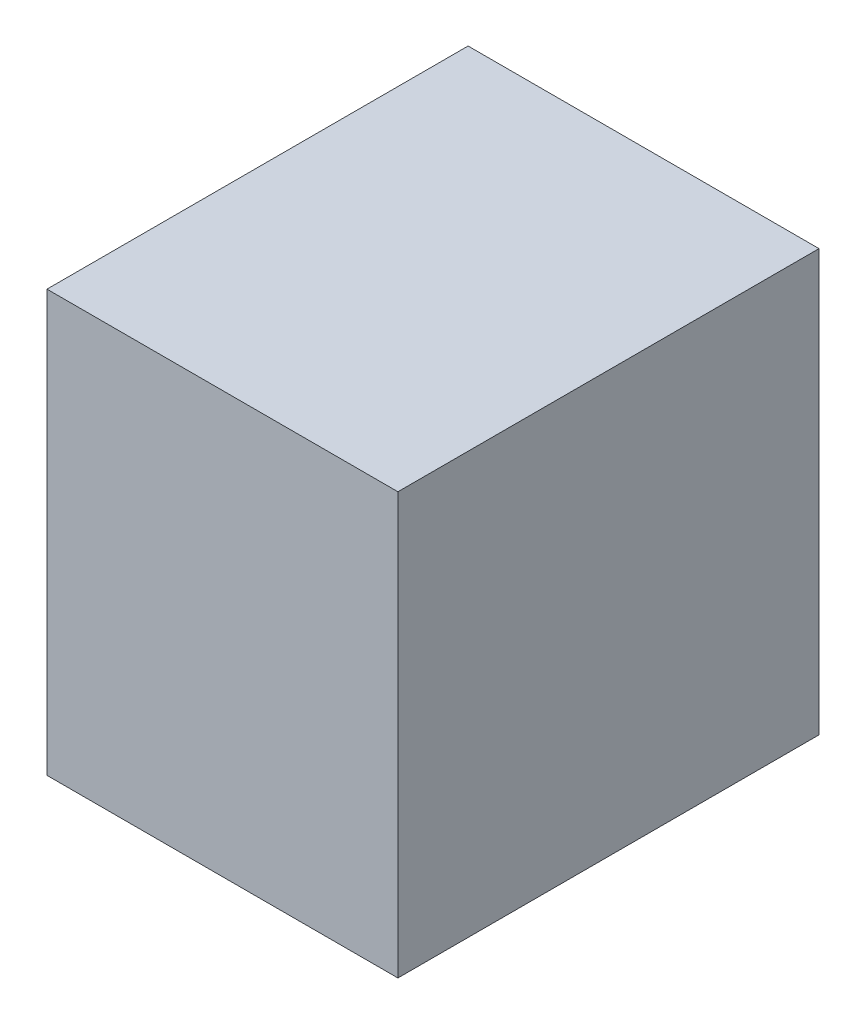
SolidWorks part; units mm, degrees
material "AISI 1035 Сталь (SS)"
ref_plane "Спереди" through (0, 0, 0) normal (0, 0, 1) x (1, 0, 0)
ref_plane "Сверху" through (0, 0, 0) normal (0, 1, 0) x (1, 0, 0)
ref_plane "Справа" through (0, 0, 0) normal (1, 0, 0) x (0, 0, -1)
sketch "Эскиз1" plane through (0, 0, 0) normal (0, 0, 1) x (1, 0, 0)
  line L1 (44.0503, 37.6311) -> (69.0503, 37.6311)
  line L2 (44.0503, 37.6311) -> (44.0503, 7.6311)
  line L3 (44.0503, 7.6311) -> (69.0503, 7.6311)
  line L4 (69.0503, 37.6311) -> (69.0503, 7.6311)
  dimension "D1" = 25
  dimension "D2" = 30
extrude "Бобышка-Вытянуть1" add sketch "Эскиз1" along normal blind 30
